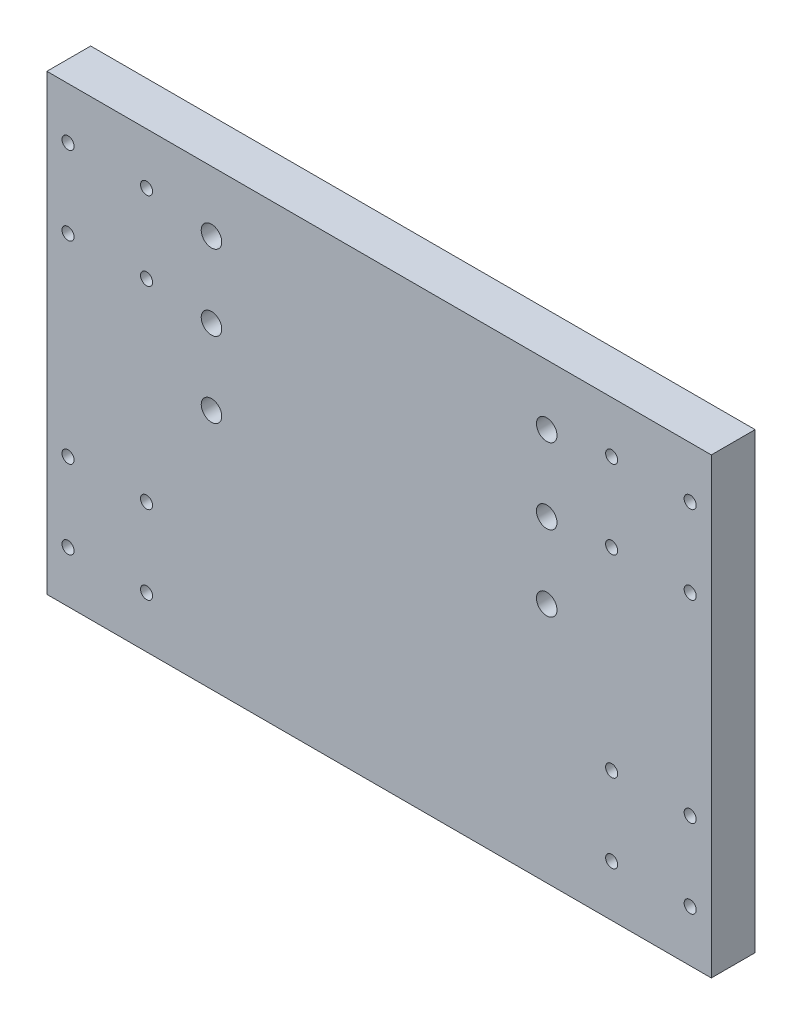
SolidWorks part; units mm, degrees
ref_plane "Plan de face" through (0, 0, 0) normal (0, 0, 1) x (1, 0, 0)
ref_plane "Plan de dessus" through (0, 0, 0) normal (0, 1, 0) x (1, 0, 0)
ref_plane "Plan de droite" through (0, 0, 0) normal (1, 0, 0) x (0, 0, -1)
sketch "Esquisse1" plane through (0, 0, 0) normal (0, 0, 1) x (1, 0, 0)
  line L1 (0, 0) -> (220, 0)
  line L2 (0, 0) -> (0, 150)
  line L3 (0, 150) -> (220, 150)
  line L4 (220, 0) -> (220, 150)
  dimension "D1" = 220
  dimension "D2" = 150
extrude "Boss.-Extru.1" add sketch "Esquisse1" along normal blind 14.5
sketch "Esquisse2" plane through (0, 0, 14.5) normal (0, 0, 1) x (1, 0, 0)
  line L0 (110, 0) -> (110, 150) construction
  line L1 (0, 0) -> (220, 0) construction
  line L2 (220, 150) -> (0, 150) construction
  line L3 (110, 75) -> (0, 75) construction
  line L4 (0, 150) -> (0, 0) construction
  line L5 (33, 43) -> (33, 30) construction
  line L6 (33, 30) -> (7, 30) construction
  line L7 (20, 30) -> (20, 27.1633) construction
  line L8 (7, 43) -> (7, 30) construction
  line L9 (213, 43) -> (213, 30) construction
  line L10 (200, 30) -> (200, 27.1633) construction
  line L11 (187, 30) -> (213, 30) construction
  line L12 (187, 43) -> (187, 30) construction
  line L13 (187, 107) -> (187, 120) construction
  line L14 (187, 120) -> (213, 120) construction
  line L15 (200, 120) -> (200, 122.8367) construction
  line L16 (213, 107) -> (213, 120) construction
  line L17 (7, 107) -> (7, 120) construction
  line L18 (20, 120) -> (20, 122.8367) construction
  line L19 (33, 120) -> (7, 120) construction
  line L20 (33, 107) -> (33, 120) construction
  circle A0 centre (33, 43) radius 2
  circle A1 centre (33, 17) radius 2
  circle A2 centre (7, 17) radius 2
  circle A3 centre (7, 43) radius 2
  circle A4 centre (213, 43) radius 2
  circle A5 centre (213, 17) radius 2
  circle A6 centre (187, 17) radius 2
  circle A7 centre (187, 43) radius 2
  circle A8 centre (187, 107) radius 2
  circle A9 centre (187, 133) radius 2
  circle A10 centre (213, 133) radius 2
  circle A11 centre (213, 107) radius 2
  circle A12 centre (7, 107) radius 2
  circle A13 centre (7, 133) radius 2
  circle A14 centre (33, 133) radius 2
  circle A15 centre (33, 107) radius 2
  dimension "D1" = 4
  dimension "D2" = 26
  dimension "D3" = 26
  dimension "D4" = 45
  dimension "D5" = 90
extrude "Enlèv. mat.-Extru.1" cut sketch "Esquisse2" against normal through all both and the other way through all
sketch "Esquisse3" plane through (0, 0, 0) normal (0, 0, 1) x (1, 0, 0)
  line L0 (0, 75) -> (110, 75) construction
  line L1 (0, 150) -> (0, 0) construction
  line L2 (110, 75) -> (110, 0) construction
  line L3 (0, 0) -> (220, 0) construction
  circle A0 centre (7, 17) radius 4
  circle A1 centre (33, 17) radius 4
  circle A2 centre (33, 43) radius 4
  circle A3 centre (7, 43) radius 4
  circle A4 centre (213, 43) radius 4
  circle A5 centre (187, 43) radius 4
  circle A6 centre (187, 17) radius 4
  circle A7 centre (213, 17) radius 4
  circle A8 centre (213, 133) radius 4
  circle A9 centre (187, 133) radius 4
  circle A10 centre (187, 107) radius 4
  circle A11 centre (213, 107) radius 4
  circle A12 centre (7, 107) radius 4
  circle A13 centre (33, 107) radius 4
  circle A14 centre (33, 133) radius 4
  circle A15 centre (7, 133) radius 4
  dimension "D1" = 8
extrude "Enlèv. mat.-Extru.2" cut sketch "Esquisse3" along normal blind 4
sketch "Esquisse4" plane through (0, 0, 0) normal (0, 0, -1) x (-1, 0, 0)
  line L0 (-110, 0) -> (-110, 150) construction
  line L1 (0, 0) -> (-220, 0) construction
  line L2 (-220, 150) -> (0, 150) construction
  line L3 (-165.5, 130) -> (-110, 130) construction
  line L4 (-165.5, 130) -> (-165.5, 105) construction
  line L5 (-165.5, 105) -> (-110, 105) construction
  line L6 (-54.5, 130) -> (-54.5, 105) construction
  circle A0 centre (-165.5, 130) radius 3.4
  circle A1 centre (-165.5, 105) radius 3.4
  circle A2 centre (-165.5, 80) radius 3.4
  circle A3 centre (-54.5, 80) radius 3.4
  circle A4 centre (-54.5, 105) radius 3.4
  circle A5 centre (-54.5, 130) radius 3.4
  dimension "D1" = 6.8
  dimension "D2" = 25
  dimension "D3" = 55.5
  dimension "D4" = 45
extrude "Enlèv. mat.-Extru.3" cut sketch "Esquisse4" against normal through all both and the other way through all
